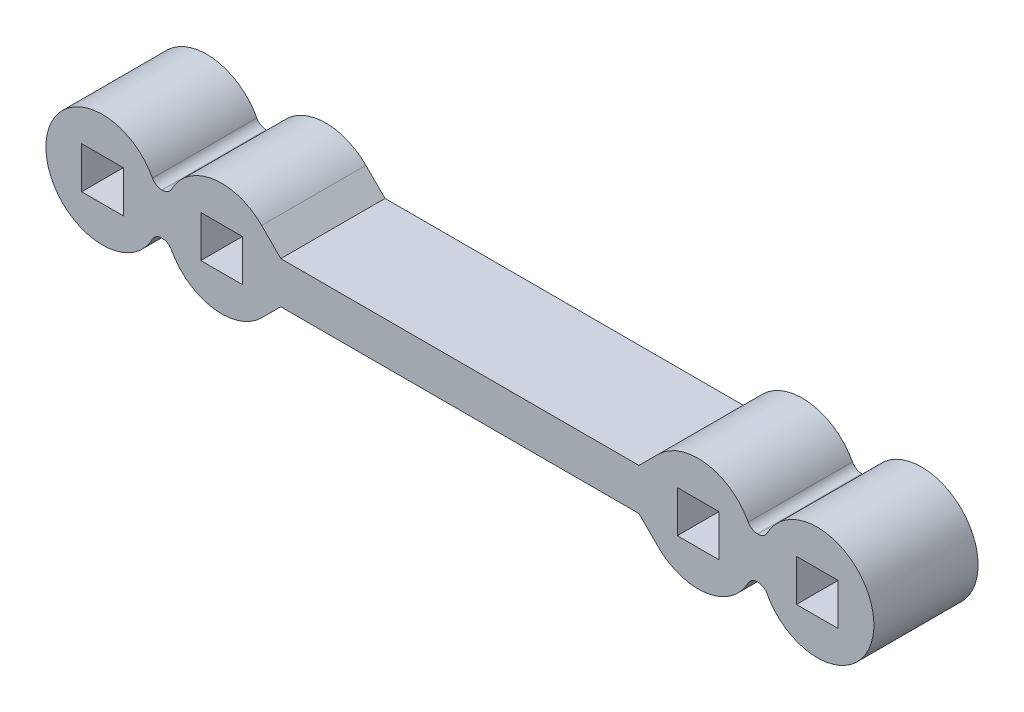
SolidWorks part; units mm, degrees
ref_plane "Plano frontal" through (0, 0, 0) normal (0, 0, 1) x (1, 0, 0)
ref_plane "Plano superior" through (0, 0, 0) normal (0, 1, 0) x (1, 0, 0)
ref_plane "Plano direito" through (0, 0, 0) normal (1, 0, 0) x (0, 0, -1)
sketch "Esboço1" plane through (0, 0, 0) normal (0, 0, 1) x (1, 0, 0)
  line L0 (13.313, 2.687) -> (12.026, 1.4)
  line L1 (0, -1.4) -> (0, 1.4) construction
  line L2 (-12.026, 1.4) -> (12.026, 1.4)
  line L3 (-27.8, 0) -> (27.8, 0) construction
  line L4 (14.6, 1.4) -> (17.4, 1.4)
  line L5 (14.6, 1.4) -> (14.6, -1.4)
  line L6 (14.6, -1.4) -> (17.4, -1.4)
  line L7 (17.4, 1.4) -> (17.4, -1.4)
  line L8 (14.6, 1.4) -> (17.4, -1.4) construction
  line L9 (14.6, -1.4) -> (17.4, 1.4) construction
  line L10 (19.9799, 1.4) -> (20.0201, 1.4)
  line L11 (16, 0) -> (24, 0) construction
  line L12 (22.6, 1.4) -> (25.4, 1.4)
  line L13 (22.6, 1.4) -> (25.4, -1.4) construction
  line L14 (22.6, 1.4) -> (22.6, -1.4)
  line L15 (25.4, 1.4) -> (25.4, -1.4)
  line L16 (22.6, -1.4) -> (25.4, -1.4)
  line L17 (22.6, -1.4) -> (25.4, 1.4) construction
  line L18 (19.9799, -1.4) -> (20.0201, -1.4)
  line L19 (-12.026, -1.4) -> (12.026, -1.4)
  line L20 (13.313, -2.687) -> (12.026, -1.4)
  line L21 (-22.6, -1.4) -> (-25.4, 1.4) construction
  line L22 (-22.6, 1.4) -> (-25.4, -1.4) construction
  line L23 (-16, 0) -> (-24, 0) construction
  line L24 (-14.6, -1.4) -> (-17.4, 1.4) construction
  line L25 (-14.6, 1.4) -> (-17.4, -1.4) construction
  line L26 (-13.313, -2.687) -> (-12.026, -1.4)
  line L27 (-19.9799, -1.4) -> (-20.0201, -1.4)
  line L28 (-22.6, -1.4) -> (-25.4, -1.4)
  line L29 (-25.4, 1.4) -> (-25.4, -1.4)
  line L30 (-22.6, 1.4) -> (-22.6, -1.4)
  line L31 (-22.6, 1.4) -> (-25.4, 1.4)
  line L32 (-19.9799, 1.4) -> (-20.0201, 1.4)
  line L33 (-17.4, 1.4) -> (-17.4, -1.4)
  line L34 (-14.6, -1.4) -> (-17.4, -1.4)
  line L35 (-14.6, 1.4) -> (-14.6, -1.4)
  line L36 (-14.6, 1.4) -> (-17.4, 1.4)
  line L37 (-13.313, 2.687) -> (-12.026, 1.4)
  arc A0 (19.3608, 1.7733) -> (13.313, 2.687) centre (16, 0) ccw
  arc A1 (20.6392, -1.7733) -> (20.6392, 1.7733) centre (24, 0) ccw
  arc A2 (19.9799, -1.4) -> (19.3608, -1.7733) centre (19.9799, -2.1) ccw
  arc A3 (20.0201, 1.4) -> (20.6392, 1.7733) centre (20.0201, 2.1) ccw
  arc A4 (19.9799, 1.4) -> (19.3608, 1.7733) centre (19.9799, 2.1) cw
  arc A5 (20.0201, -1.4) -> (20.6392, -1.7733) centre (20.0201, -2.1) cw
  arc A6 (19.3608, -1.7733) -> (13.313, -2.687) centre (16, 0) cw
  arc A7 (-19.3608, -1.7733) -> (-13.313, -2.687) centre (-16, 0) ccw
  arc A8 (-20.0201, -1.4) -> (-20.6392, -1.7733) centre (-20.0201, -2.1) ccw
  arc A9 (-19.9799, 1.4) -> (-19.3608, 1.7733) centre (-19.9799, 2.1) ccw
  arc A10 (-20.0201, 1.4) -> (-20.6392, 1.7733) centre (-20.0201, 2.1) cw
  arc A11 (-19.9799, -1.4) -> (-19.3608, -1.7733) centre (-19.9799, -2.1) cw
  arc A12 (-20.6392, -1.7733) -> (-20.6392, 1.7733) centre (-24, 0) cw
  arc A13 (-19.3608, 1.7733) -> (-13.313, 2.687) centre (-16, 0) cw
  point P43 (0, 0)
  dimension "D1" = 0.7
extrude "Ressalto-extrusão1" add sketch "Esboço1" along normal blind 7
